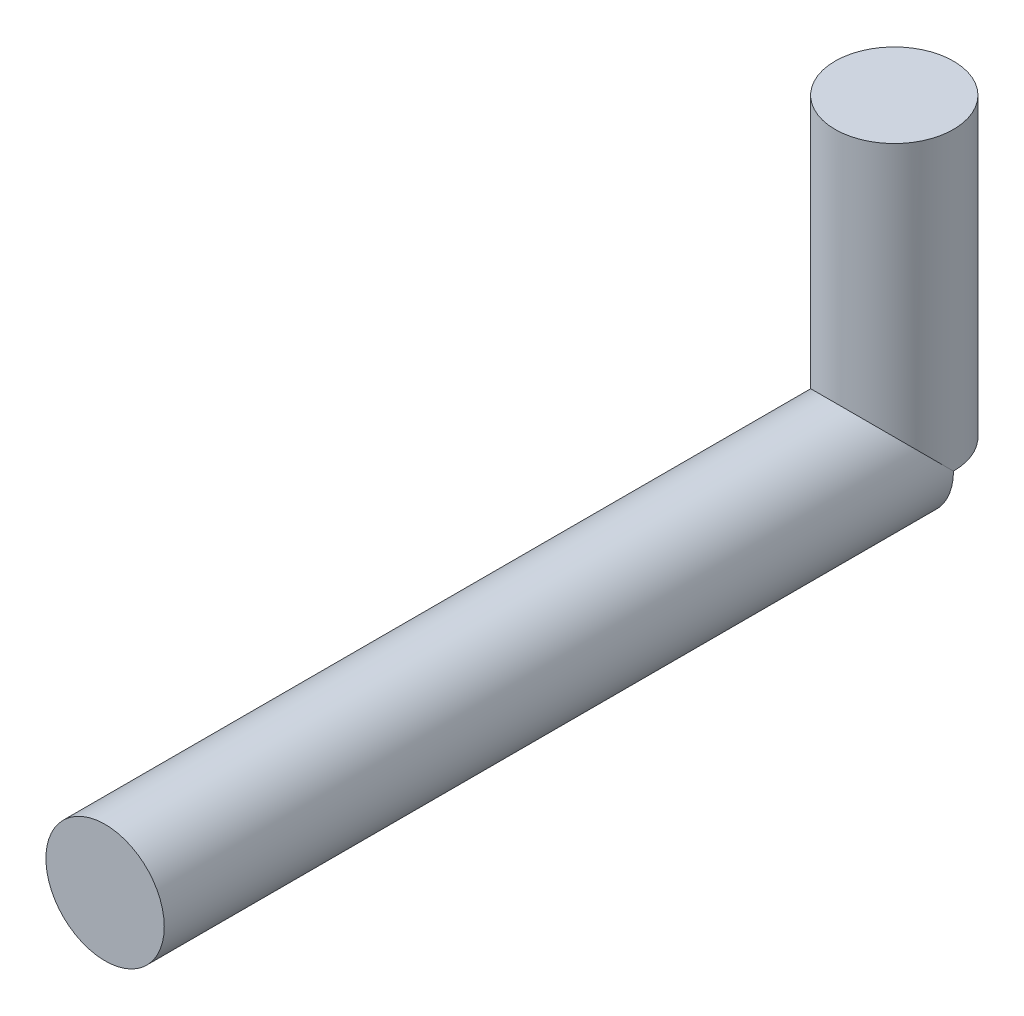
SolidWorks part; units mm, degrees
ref_plane "前视基准面" through (0, 0, 0) normal (0, 0, 1) x (1, 0, 0)
ref_plane "上视基准面" through (0, 0, 0) normal (0, 1, 0) x (1, 0, 0)
ref_plane "右视基准面" through (0, 0, 0) normal (1, 0, 0) x (0, 0, -1)
sketch "草图1" plane through (0, 0, 0) normal (0, 0, 1) x (1, 0, 0)
  line L0 (0, 0.3) -> (0, -0.3) construction
  circle A0 centre (0, 0) radius 0.3
extrude "凸台-拉伸1" add sketch "草图1" along normal blind 4
pattern_linear "阵列(线性)1" [suppressed] count 2 spacing 2.54 along (0, -1, 0)
sketch "草图4" plane through (0, 0, 0) normal (0, 1, 0) x (1, 0, 0)
  circle A0 centre (0, 0) radius 0.3
extrude "凸台-拉伸5" add sketch "草图4" along normal blind 1.5
